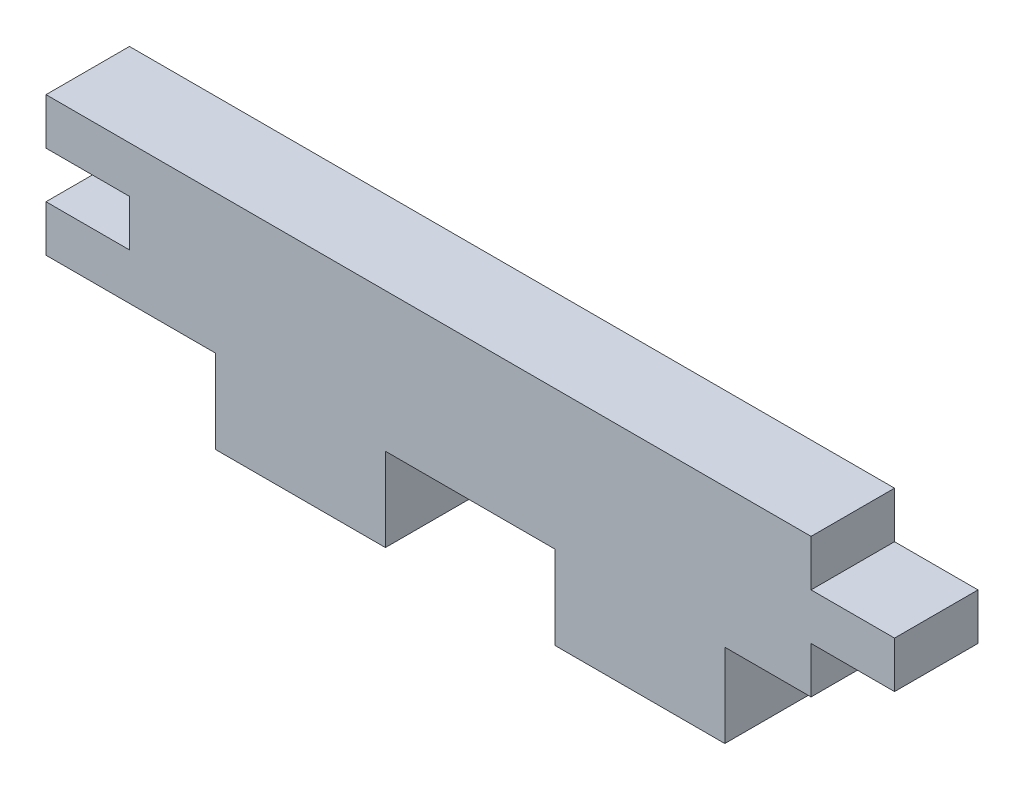
SolidWorks part; units mm, degrees
ref_plane "Front Plane" through (0, 0, 0) normal (0, 0, 1) x (1, 0, 0)
ref_plane "Top Plane" through (0, 0, 0) normal (0, 1, 0) x (1, 0, 0)
ref_plane "Right Plane" through (0, 0, 0) normal (1, 0, 0) x (0, 0, -1)
sketch "Sketch1" plane through (0, 0, 0) normal (0, 0, 1) x (1, 0, 0)
  line L1 (0, 0) -> (154.94, 0)
  line L2 (0, 0) -> (0, 40.64)
  line L3 (0, 40.64) -> (154.94, 40.64)
  line L4 (154.94, 0) -> (154.94, 40.64)
  dimension "D1" = 154.94
  dimension "D2" = 40.64
extrude "Boss-Extrude1" add sketch "Sketch1" along normal blind 15.24
sketch "Sketch2" plane through (0, 0, 15.24) normal (0, 0, 1) x (1, 0, 0)
  line L0 (0, 40.64) -> (0, 0) construction
  line L1 (0, 15.24) -> (30.988, 15.24)
  line L2 (0, 15.24) -> (0, 0)
  line L3 (0, 0) -> (30.988, 0)
  line L4 (30.988, 15.24) -> (30.988, 0)
  line L5 (0, 0) -> (154.94, 0) construction
  line L6 (30.988, 15.24) -> (61.976, 15.24) construction
  line L7 (61.976, 0) -> (92.964, 0)
  line L8 (61.976, 0) -> (61.976, 15.24)
  line L9 (61.976, 15.24) -> (92.964, 15.24)
  line L10 (92.964, 0) -> (92.964, 15.24)
  line L11 (154.94, 0) -> (123.952, 0)
  line L12 (154.94, 0) -> (154.94, 15.24)
  line L13 (154.94, 15.24) -> (123.952, 15.24)
  line L14 (123.952, 0) -> (123.952, 15.24)
  line L15 (92.964, 15.24) -> (123.952, 15.24) construction
  dimension "D1" = 15.24
extrude "Cut-Extrude1" cut sketch "Sketch2" against normal through all
sketch "Sketch3" plane through (0, 0, 15.24) normal (0, 0, 1) x (1, 0, 0)
  line L0 (0, 40.64) -> (0, 15.24) construction
  line L1 (0, 32.1733) -> (15.24, 32.1733)
  line L2 (0, 32.1733) -> (0, 23.7067)
  line L3 (0, 23.7067) -> (15.24, 23.7067)
  line L4 (15.24, 32.1733) -> (15.24, 23.7067)
  line L5 (15.24, 32.1733) -> (15.24, 40.64) construction
  line L6 (154.94, 40.64) -> (0, 40.64) construction
  line L7 (15.24, 23.7067) -> (15.24, 15.24) construction
  line L8 (30.988, 15.24) -> (0, 15.24) construction
  line L9 (139.7, 32.1733) -> (139.7, 23.7067) construction
  line L10 (154.94, 40.64) -> (139.7, 40.64)
  line L11 (154.94, 40.64) -> (154.94, 32.1733)
  line L12 (154.94, 32.1733) -> (139.7, 32.1733)
  line L13 (139.7, 40.64) -> (139.7, 32.1733)
  line L14 (154.94, 15.24) -> (139.7, 15.24)
  line L15 (154.94, 15.24) -> (154.94, 23.7067)
  line L16 (154.94, 23.7067) -> (139.7, 23.7067)
  line L17 (139.7, 15.24) -> (139.7, 23.7067)
  dimension "D1" = 15.24
  dimension "D2" = 15.24
extrude "Cut-Extrude2" cut sketch "Sketch3" against normal through all
equation "\"MDF\"= .3"
equation "\"Foamcore\"= .1"
equation "\"GMaterial\"= .6"
equation "\"CutDistance\" = .1"
equation "\"D1@Sketch1\"=\"GMaterial\"+5.5"
equation "\"D2@Sketch1\"=\"GMaterial\" + 1"
equation "\"D1@Boss-Extrude1\"=\"GMaterial\""
equation "\"D1@Sketch2\"=\"GMaterial\""
equation "\"D1@Sketch3\"=\"GMaterial\""
equation "\"D2@Sketch3\"=\"GMaterial\""
